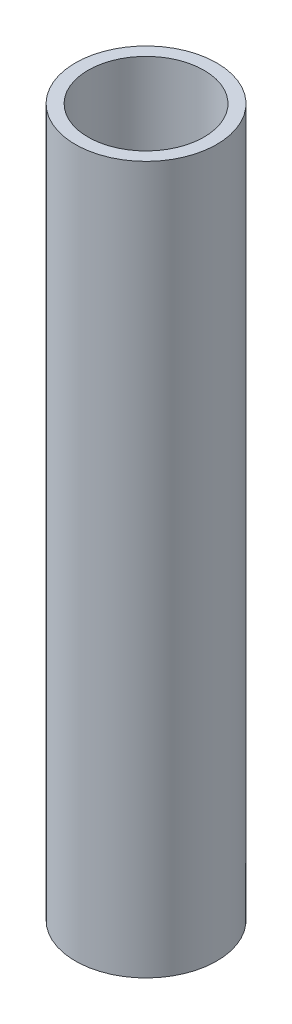
SolidWorks part; units mm, degrees
ref_plane "Front Plane" through (0, 0, 0) normal (0, 0, 1) x (1, 0, 0)
ref_plane "Top Plane" through (0, 0, 0) normal (0, 1, 0) x (1, 0, 0)
ref_plane "Right Plane" through (0, 0, 0) normal (1, 0, 0) x (0, 0, -1)
sketch "Sketch1" plane through (0, 0, 0) normal (0, 0, 1) x (1, 0, 0)
  line L0 (12.6962, 127) -> (10.4102, 127)
  line L1 (10.4102, 127) -> (10.4102, 0)
  line L2 (10.4102, 0) -> (12.6962, 0)
  line L3 (12.6962, 0) -> (12.6962, 127)
  line L4 (0, 127) -> (0, 0) construction
revolve "Revolve1" add sketch "Sketch1" angle 360 about L4
